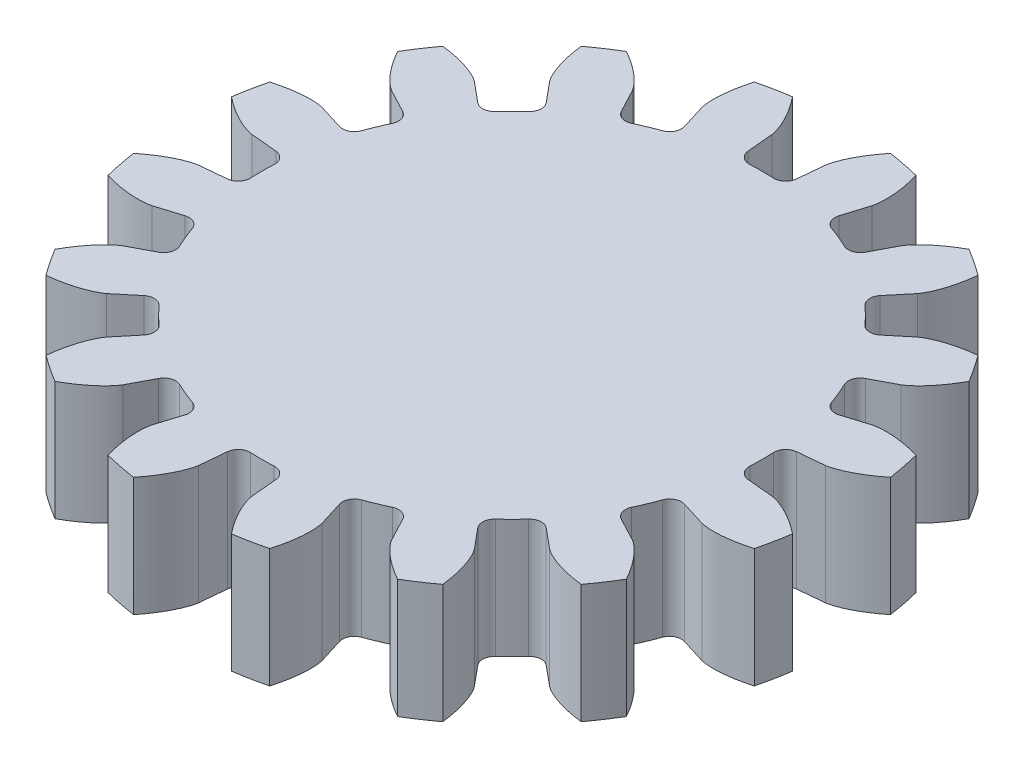
SolidWorks part; units mm, degrees
ref_plane "Front Plane" through (0, 0, 0) normal (0, 0, 1) x (1, 0, 0)
ref_plane "Top Plane" through (0, 0, 0) normal (0, 1, 0) x (1, 0, 0)
ref_plane "Right Plane" through (0, 0, 0) normal (1, 0, 0) x (0, 0, -1)
sketch "Sketch1" plane through (0, 0, 0) normal (0, 1, 0) x (1, 0, 0)
  circle A0 centre (0, 0) radius 7.112
  dimension "D1" = 14.224
extrude "Boss-Extrude1" add sketch "Sketch1" along normal blind 2.54
sketch "Sketch2" plane through (0, 2.54, 0) normal (0, 1, 0) x (1, 0, 0)
  line L0 (0, 0) -> (6.1214, 0.5687) construction
  line L1 (0, 0) -> (6.1214, -0.5687) construction
  line L2 (6.1214, 0.5687) -> (5.3111, 0.4934)
  line L3 (6.1214, -0.5687) -> (5.3111, -0.4934)
  circle A0 centre (0, 0) radius 7.112
  circle A1 centre (0, 0) radius 6.35
  circle A2 centre (0, 0) radius 6.096
  circle A3 centre (0, 0) radius 5.334
  arc A4 (5.3111, 0.4934) -> (5.3111, -0.4934) centre (0, 0) cw
  spline S0 degree 4 poles (6.1214, 0.5687) (6.1258, 0.5691) (6.1342, 0.5703) (6.1478, 0.5726) (6.1745, 0.5781) (6.2045, 0.5855) (6.2383, 0.5951) (6.2743, 0.6065) (6.3049, 0.617) (6.3354, 0.6282) (6.3655, 0.64) (6.4019, 0.6549) (6.4454, 0.6739) (6.4958, 0.6975) (6.5525, 0.726) (6.6098, 0.7569) (6.6657, 0.7888) (6.7218, 0.8227) (6.7756, 0.8567) (6.831, 0.8938) (6.8819, 0.929) (6.9382, 0.9703) (6.9834, 1.0041) (7.0424, 1.0508) (7.0771, 1.079) (7.1173, 1.1127) (7.1351, 1.128) (7.146, 1.1374) knots 0 0 0 0 0 0.015084 0.028532 0.04661 0.092111 0.119476 0.146842 0.174209 0.201575 0.228941 0.256307 0.307035 0.361767 0.4165 0.471232 0.525964 0.580697 0.635429 0.690161 0.744894 0.799626 0.854358 0.909091 0.954545 1 1 1 1 1 construction
  spline S1 degree 4 poles (6.1214, 0.5687) (6.1258, 0.5691) (6.1342, 0.5703) (6.1478, 0.5726) (6.1745, 0.5781) (6.2045, 0.5855) (6.2383, 0.5951) (6.2743, 0.6065) (6.3049, 0.617) (6.3354, 0.6282) (6.3655, 0.64) (6.4019, 0.6549) (6.4454, 0.6739) (6.4958, 0.6975) (6.5525, 0.726) (6.6098, 0.7569) (6.6657, 0.7888) (6.7218, 0.8227) (6.7756, 0.8567) (6.831, 0.8938) (6.8819, 0.929) (6.9382, 0.9703) (6.9834, 1.0041) (7.0296, 1.0407) (7.052, 1.0587) (7.0635, 1.0681) knots 0 0 0 0 0 0.015084 0.028532 0.04661 0.092111 0.119476 0.146842 0.174209 0.201575 0.228941 0.256307 0.307035 0.361767 0.4165 0.471232 0.525964 0.580697 0.635429 0.690161 0.744894 0.799626 0.854358 0.909091 0.909091 0.909091 0.909091 0.909091
  spline S2 degree 4 poles (6.1214, -0.5687) (6.1258, -0.5691) (6.1342, -0.5703) (6.1478, -0.5726) (6.1745, -0.5781) (6.2045, -0.5855) (6.2383, -0.5951) (6.2743, -0.6065) (6.3049, -0.617) (6.3354, -0.6282) (6.3655, -0.64) (6.4019, -0.6549) (6.4454, -0.6739) (6.4958, -0.6975) (6.5525, -0.726) (6.6098, -0.7569) (6.6657, -0.7888) (6.7218, -0.8227) (6.7756, -0.8567) (6.831, -0.8938) (6.8819, -0.929) (6.9382, -0.9703) (6.9834, -1.0041) (7.0424, -1.0508) (7.0771, -1.079) (7.1173, -1.1127) (7.1351, -1.128) (7.146, -1.1374) knots 0 0 0 0 0 0.015084 0.028532 0.04661 0.092111 0.119476 0.146842 0.174209 0.201575 0.228941 0.256307 0.307035 0.361767 0.4165 0.471232 0.525964 0.580697 0.635429 0.690161 0.744894 0.799626 0.854358 0.909091 0.954545 1 1 1 1 1 construction
  spline S3 degree 4 poles (6.1214, -0.5687) (6.1258, -0.5691) (6.1342, -0.5703) (6.1478, -0.5726) (6.1745, -0.5781) (6.2045, -0.5855) (6.2383, -0.5951) (6.2743, -0.6065) (6.3049, -0.617) (6.3354, -0.6282) (6.3655, -0.64) (6.4019, -0.6549) (6.4454, -0.6739) (6.4958, -0.6975) (6.5525, -0.726) (6.6098, -0.7569) (6.6657, -0.7888) (6.7218, -0.8227) (6.7756, -0.8567) (6.831, -0.8938) (6.8819, -0.929) (6.9382, -0.9703) (6.9834, -1.0041) (7.0296, -1.0407) (7.052, -1.0587) (7.0635, -1.0681) knots 0 0 0 0 0 0.015084 0.028532 0.04661 0.092111 0.119476 0.146842 0.174209 0.201575 0.228941 0.256307 0.307035 0.361767 0.4165 0.471232 0.525964 0.580697 0.635429 0.690161 0.744894 0.799626 0.854358 0.909091 0.909091 0.909091 0.909091 0.909091
  dimension "D1" = 14.224
  dimension "D2" = 12.7
  dimension "D3" = 12.192
  dimension "D4" = 10.668
extrude "Cut-Extrude1" cut sketch "Sketch2" against normal blind 2.54 contours A1 S3 A0 S1 | L3 S3 A1 S1 L2 A2 | A3 L3 A2 L2
fillet "Fillet1" radius 0.254 2 edges at (5.3111, 1.27, 0.4934) (5.3111, 1.27, -0.4934)
pattern_circular "CirPattern1" count 16 over 360 about axis through (0, 2.54, 0) along (0, 1, 0) of "Fillet1", "Cut-Extrude1"
equation "\"DiametralPitch\"= 32"
equation "\"NumTeeth\"= 16"
equation "\"PressureAngle\"= 14.5deg"
equation "\"Addendum\"= 1 / \"DiametralPitch\""
equation "\"Dedendum\"= 1.25 / \"DiametralPitch\""
equation "\"WorkingDepth\"= 2 / \"DiametralPitch\""
equation "\"WholeDepth\"= 2.25 / \"DiametralPitch\""
equation "\"Clearance\"= 0.25 / \"DiametralPitch\""
equation "\"ToothThickness\"= 1.5708 / \"DiametralPitch\""
equation "\"CircularPitch\"= pi / \"DiametralPitch\""
equation "\"PitchCircle\"= \"NumTeeth\" / \"DiametralPitch\""
equation "\"OutsideDiameter\"= ( \"NumTeeth\" + 2 ) / \"DiametralPitch\""
equation "\"Fillet\"= \"Clearance\" * cos ( \"PressureAngle\" ) * tan ( ( 90 + \"PressureAngle\" ) / 2 )"
equation "\"AddendumCircle\"= \"PitchCircle\" + ( 2 * \"Addendum\" )"
equation "\"DedendumCircle\"= \"PitchCircle\" - ( 2 * \"Dedendum\" )"
equation "\"BaseCircle\"= \"PitchCircle\" * cos ( \"PressureAngle\" )"
equation "\"PitchAngle\"= 360deg / \"NumTeeth\""
equation "\"Alpha\"= sqr ( \"PitchCircle\" ^ 2 - \"BaseCircle\" ^ 2 ) / \"BaseCircle\" * 180 / PI - \"PressureAngle\""
equation "\"Beta\"= ( \"PitchAngle\" / 4 - \"Alpha\" )"
equation "\"Phi\"= sqr ( ( \"AddendumCircle\" / 2 ) ^ 2 - ( \"BaseCircle\" / 2 ) ^ 2 ) / ( \"BaseCircle\" / 2 )"
